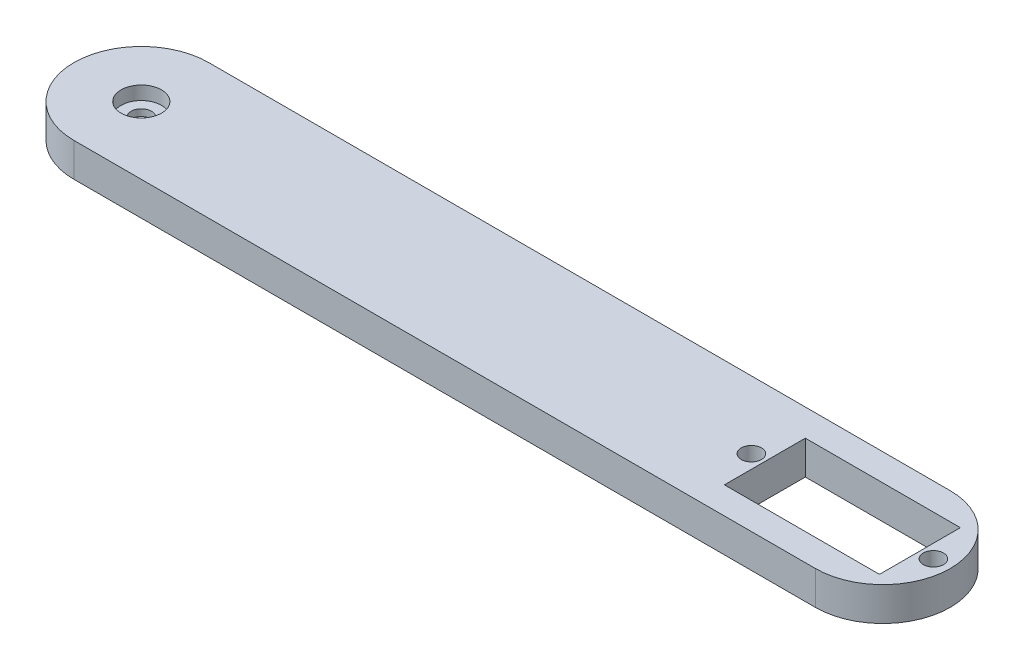
SolidWorks part; units mm, degrees
ref_plane "Front Plane" through (0, 0, 0) normal (0, 0, 1) x (1, 0, 0)
ref_plane "Top Plane" through (0, 0, 0) normal (0, 1, 0) x (1, 0, 0)
ref_plane "Right Plane" through (0, 0, 0) normal (1, 0, 0) x (0, 0, -1)
sketch "Sketch1" plane through (0, 0, 0) normal (0, 1, 0) x (1, 0, 0)
  line L1 (-40, 10) -> (40, 10)
  line L3 (-40, -10) -> (40, -10)
  line L6 (-40, 10) -> (-70, 10)
  line L8 (-40, -10) -> (-70, -10)
  arc A0 (40, -10) -> (40, 10) centre (40, 0) ccw
  arc A3 (-70, 10) -> (-70, -10) centre (-70, 0) ccw
  point P0 (0, 0)
  point P10 (-70, 10)
  dimension "D1" = 80
  dimension "D2" = 20
extrude "Boss-Extrude1" add sketch "Sketch1" along normal blind 5
sketch "Sketch3" plane through (0, 5, 0) normal (0, 1, 0) x (1, 0, 0)
  line L0 (40, 10) -> (40, -10)
  line L2 (22.5, 6) -> (45.5, 6)
  line L3 (22.5, 6) -> (22.5, -6)
  line L4 (22.5, -6) -> (45.5, -6)
  line L5 (45.5, 6) -> (45.5, -6)
  circle A0 centre (47.5, 0) radius 1.5
  circle A1 centre (20.5, 0) radius 1.5
  point P4 (40, 0)
  point P5 (47.5, 0)
  point P6 (45.5, 0)
  point P7 (45.5, 6)
  point P8 (45.5, -6)
  point P9 (22.5, 6)
  point P16 (20.5, 0)
  dimension "D5" = 3
  dimension "D7" = 3
  dimension "D1" = 5.5
  dimension "7.5" = 7.5
  dimension "D2" = 6
  dimension "D3" = 6
  dimension "D4" = 23
  dimension "D6" = 2
extrude "Cut-Extrude1" cut sketch "Sketch3" against normal through all contours L3 L4 L0 L2 | L5 L2 L0 L4 | A1 | A0
sketch "Sketch5" plane through (0, 5, 0) normal (0, 1, 0) x (1, 0, 0)
  circle A0 centre (-70, 0) radius 3
  point P0 (-70, 0)
  dimension "D1" = 6
extrude "Cut-Extrude2" cut sketch "Sketch5" against normal blind 2
sketch "Sketch6" plane through (0, 0, 0) normal (0, -1, 0) x (1, 0, 0)
  line L0 (-70, 10) -> (-70, -10)
  line L2 (-50, 3) -> (-70, 6.6047)
  line L3 (-90, 3) -> (-70, 6.6047)
  line L4 (-90, -3) -> (-70, -6.5)
  line L5 (-70, -6.5) -> (-50, -3)
  circle A0 centre (-70, 0) radius 6.5
  circle A1 centre (-50, 0) radius 3
  circle A2 centre (-90, 0) radius 3
  point P7 (-90, 0)
  point P8 (-50, 0)
  line M6 (22.5, -6) -> (22.5, 6)
  arc M11 (-70, 10) -> (-70, -10) centre (-70, 0) ccw
  dimension "D1" = 13
  dimension "D4" = 6
  dimension "D5" = 6
  dimension "D2" = 20
  dimension "D3" = 20
extrude "Cut-Extrude3" cut sketch "Sketch6" against normal blind 2 contours A1 L2 A0 L5 | L5 A0 L0 | L0 A0 L4 | A2 L4 L3 M11 | A0 L3 L4 M11 | A1 | A2 M6
sketch "Sketch8" plane through (0, 3, 0) normal (0, 1, 0) x (1, 0, 0)
  circle A0 centre (-70, 0) radius 1.5
  dimension "D1" = 3
extrude "Cut-Extrude4" cut sketch "Sketch8" against normal through all
